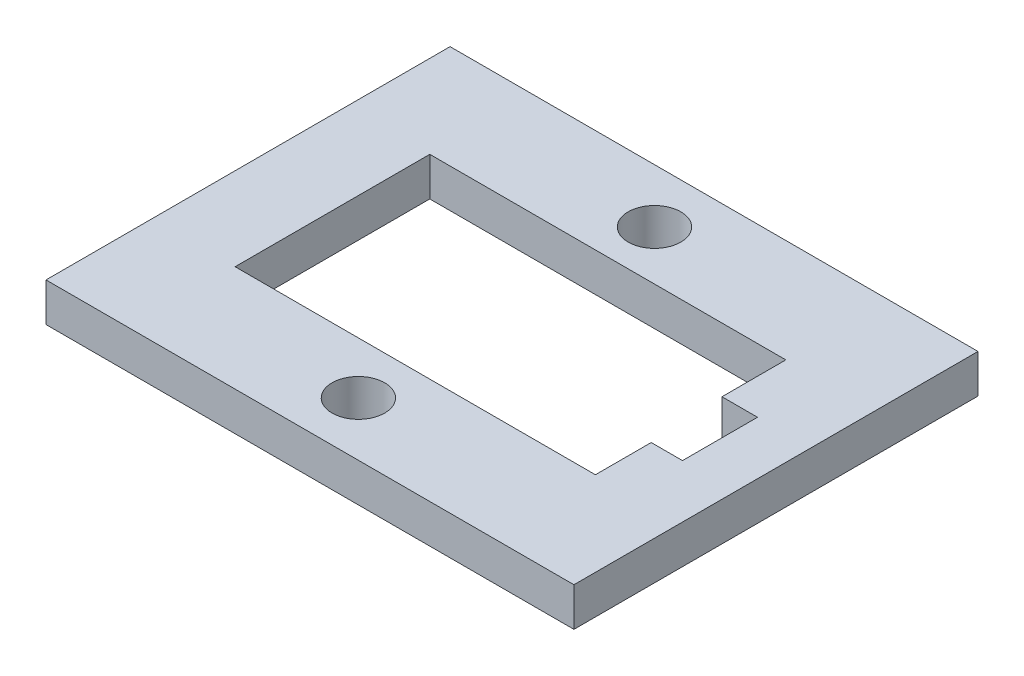
SolidWorks part; units mm, degrees
ref_plane "Front Plane" through (0, 0, 0) normal (0, 0, 1) x (1, 0, 0)
ref_plane "Top Plane" through (0, 0, 0) normal (0, 1, 0) x (1, 0, 0)
ref_plane "Right Plane" through (0, 0, 0) normal (1, 0, 0) x (0, 0, -1)
sketch "Sketch2" plane through (0, 0, 0) normal (0, 1, 0) x (1, 0, 0)
  line L0 (-11.329, 7.3335) -> (11.6851, 7.3335)
  line L1 (-16.7015, 14.0166) -> (17.4229, 14.0166)
  line L2 (-16.7015, 14.0166) -> (-16.7015, -12.1012)
  line L3 (-16.7015, -12.1012) -> (17.4229, -12.1012)
  line L4 (17.4229, 14.0166) -> (17.4229, -12.1012)
  line L5 (11.6851, 7.3335) -> (11.6851, 3.2059)
  line L6 (11.6851, 3.2059) -> (13.9825, 3.2059)
  line L7 (13.9825, 3.2059) -> (13.9825, -1.6439)
  line L8 (13.9825, -1.6439) -> (11.9606, -1.6439)
  line L9 (11.9606, -1.6439) -> (11.9606, -5.2511)
  line L10 (11.9606, -5.2511) -> (-11.329, -5.2511)
  line L11 (-11.329, -5.2511) -> (-11.329, 7.3335)
  circle A0 centre (0, 10.5289) radius 1.7
  circle A1 centre (0, -8.6112) radius 1.7
  dimension "D8" = 3.4
  dimension "D1" = 34.1244
  dimension "D2" = 26.1177
  dimension "D3" = 12.5847
  dimension "D4" = 23.2896
  dimension "D5" = 2.0219
  dimension "D6" = 4.8498
  dimension "D7" = 3.4877
  dimension "D9" = 6.683
  dimension "D10" = 3.49
  dimension "D11" = 5.3725
extrude "Boss-Extrude1" add sketch "Sketch2" along normal mid plane 2.5
